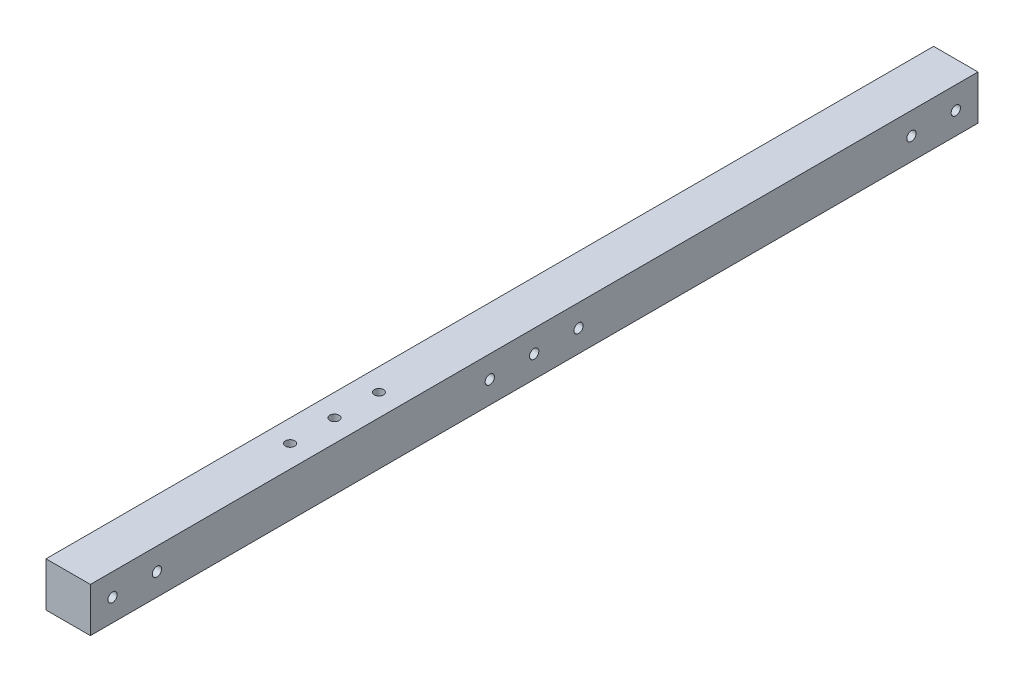
SolidWorks part; units mm, degrees
ref_plane "前视基准面" through (0, 0, 0) normal (0, 0, 1) x (1, 0, 0)
ref_plane "上视基准面" through (0, 0, 0) normal (0, 1, 0) x (1, 0, 0)
ref_plane "右视基准面" through (0, 0, 0) normal (1, 0, 0) x (0, 0, -1)
sketch "草图1" plane through (0, 0, 0) normal (0, 0, 1) x (1, 0, 0)
  line L1 (-10, 10) -> (10, 10)
  line L2 (-10, 10) -> (-10, -10)
  line L3 (-10, -10) -> (10, -10)
  line L4 (10, 10) -> (10, -10)
  line L5 (-10, 10) -> (10, -10) construction
  line L6 (-10, -10) -> (10, 10) construction
  point P0 (0, 0)
  dimension "D1" = 20
  dimension "D2" = 20
extrude "凸台-拉伸1" add sketch "草图1" along normal blind 400
sketch "草图2" plane through (10, 0, 0) normal (1, 0, 0) x (0, 0, -1)
  line L0 (-200, 10) -> (-200, -10) construction
  line L1 (-400, 10) -> (0, 10) construction
  line L2 (-400, -10) -> (0, -10) construction
  line L3 (0, -10) -> (0, 10) construction
  circle A0 centre (-10, 0) radius 2.1
  circle A1 centre (-30, 0) radius 2.1
  circle A2 centre (-390, 0) radius 2.1
  circle A3 centre (-370, 0) radius 2.1
  dimension "D1" = 4.2
  dimension "D2" = 10
  dimension "D3" = 10
  dimension "D5" = 20
  dimension "D4" = 2
extrude "切除-拉伸1" cut sketch "草图2" against normal through all
sketch "草图3" plane through (10, 0, 0) normal (1, 0, 0) x (0, 0, -1)
  line L0 (-200, 10) -> (-200, -10) construction
  line L1 (-400, 10) -> (0, 10) construction
  line L2 (-400, -10) -> (0, -10) construction
  circle A0 centre (-220, 0) radius 2.1
  circle A1 centre (-200, 0) radius 2.1
  circle A2 centre (-180, 0) radius 2.1
  dimension "D1" = 10
  dimension "D3" = 4.2
  dimension "D2" = 20
  dimension "D5" = 20
  dimension "D4" = 3
extrude "切除-拉伸2" cut sketch "草图3" against normal through all
sketch "草图4" plane through (0, -10, 0) normal (0, -1, 0) x (1, 0, 0)
  line L0 (-10, 400) -> (10, 400) construction
  line L1 (10, 400) -> (10, 0) construction
  circle A0 centre (0, 300) radius 2.1
  circle A1 centre (0, 280) radius 2.1
  circle A2 centre (0, 260) radius 2.1
  dimension "D1" = 100
  dimension "D3" = 4.2
  dimension "D4" = 3
  dimension "D5" = 20
  dimension "D2" = 10
extrude "切除-拉伸3" cut sketch "草图4" against normal through all
